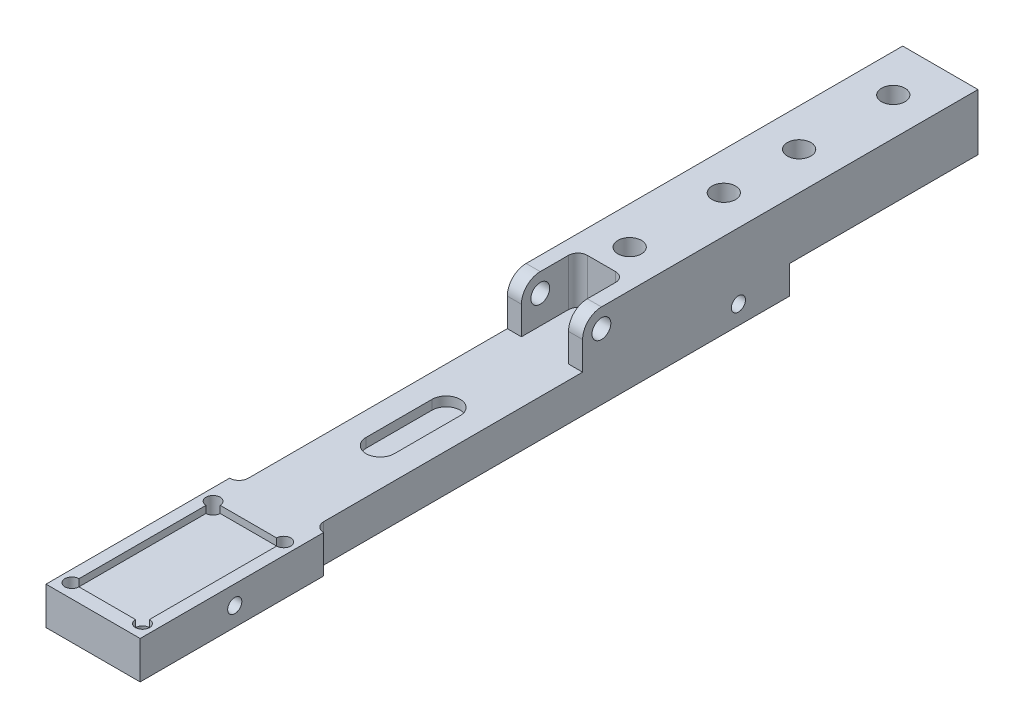
SolidWorks part; units mm, degrees
material "1060 Alloy"
ref_plane "Front Plane" through (0, 0, 0) normal (0, 0, 1) x (1, 0, 0)
ref_plane "Top Plane" through (0, 0, 0) normal (0, 1, 0) x (1, 0, 0)
ref_plane "Right Plane" through (0, 0, 0) normal (1, 0, 0) x (0, 0, -1)
sketch "Sketch1" plane through (0, 0, 0) normal (1, 0, 0) x (0, 0, -1)
  line L1 (40, -8) -> (-100, -8)
  line L2 (40, -8) -> (40, -14)
  line L3 (40, -14) -> (-100, -14)
  line L4 (-100, -8) -> (-100, -14)
  dimension "D1" = 8
  dimension "D2" = 6
  dimension "D3" = 100
  dimension "D4" = 40
extrude "Boss-Extrude1" add sketch "Sketch1" along normal mid plane 20
sketch "Sketch2" plane through (0, 0, 0) normal (1, 0, 0) x (0, 0, -1)
  line L0 (40, -8) -> (-100, -8) construction
  line L1 (-4, -8) -> (4, -8)
  line L2 (-4, -8) -> (-4, 0)
  line L3 (0, 4) -> (40, 4)
  line L4 (4, -8) -> (40, -8)
  line L5 (40, -8) -> (40, 4)
  circle A0 centre (0, 0) radius 2
  arc A1 (-4, 0) -> (0, 4) centre (0, 0) cw
  dimension "D1" = 4
  dimension "D4" = 8
  dimension "D2" = 12
  dimension "D3" = 4
extrude "Boss-Extrude2" add sketch "Sketch2" along normal mid plane 20
sketch "Sketch6" plane through (0, 0, 4) normal (0, 0, 1) x (1, 0, 0)
  line L0 (10, 4) -> (-10, 4) construction
  line L1 (-10, -8) -> (-8, -8)
  line L2 (-10, -8) -> (-10, 4)
  line L3 (-10, 4) -> (-8, 4)
  line L4 (-8, -8) -> (-8, 4)
  line L5 (0, 0) -> (0, -14.5708) construction
  line L6 (10, -8) -> (8, -8)
  line L7 (8, -8) -> (8, 4)
  line L8 (10, 4) -> (8, 4)
  line L9 (10, -8) -> (10, 4)
  dimension "D1" = 2
extrude "Cut-Extrude3" cut sketch "Sketch6" against normal through all
sketch "Sketch7" plane through (0, 4, 0) normal (0, 1, 0) x (1, 0, 0)
  line L0 (8, -4) -> (-8, -4) construction
  line L1 (-5, -4) -> (5, -4)
  line L2 (-5, -4) -> (-5, 6)
  line L3 (-3, 8) -> (3, 8)
  line L4 (5, -4) -> (5, 6)
  arc A0 (-5, 6) -> (-3, 8) centre (-3, 6) cw
  arc A1 (5, 6) -> (3, 8) centre (3, 6) ccw
  dimension "D3" = 10
  dimension "D4" = 2
  dimension "D1" = 10
  dimension "D2" = 5
extrude "Cut-Extrude4" cut sketch "Sketch7" against normal blind 10
sketch "Sketch8" plane through (0, 0, 4) normal (0, 0, 1) x (1, 0, 0)
  line L0 (8, 0) -> (8, -8) construction
  line L1 (-8, -8) -> (8, -8)
  line L2 (-8, -8) -> (-8, -6)
  line L3 (-8, -6) -> (8, -6)
  line L4 (8, -8) -> (8, -6)
  dimension "D1" = 2
extrude "Boss-Extrude3" add sketch "Sketch8" along normal blind 15
sketch "Sketch9" plane through (0, 0, 19) normal (0, 0, 1) x (1, 0, 0)
  line L0 (-10, -6) -> (10, -6)
  line L1 (-10, -8) -> (10, -8)
  line L6 (-10, -6) -> (-10, -8)
  line L10 (10, -6) -> (10, -8)
  dimension "D1" = 2
extrude "Boss-Extrude4" add sketch "Sketch9" along normal blind 81
sketch "Sketch11" plane through (0, -8, 0) normal (0, 1, 0) x (1, 0, 0)
  line L0 (-10, -59) -> (-10, -61)
  line L1 (10, 40) -> (8, 40)
  line L2 (10, 40) -> (10, -59)
  line L4 (8, 40) -> (8, -59)
  line L5 (-10, 40) -> (-8, 40)
  line L6 (-10, 40) -> (-10, -59)
  line L7 (10, -59) -> (10, -61)
  line L8 (-8, 40) -> (-8, -59)
  arc A0 (-10, -61) -> (-8, -59) centre (-10, -59) ccw
  arc A1 (8, -59) -> (10, -61) centre (10, -59) ccw
  dimension "D1" = 2
  dimension "D2" = 2
  dimension "D3" = 99
  dimension "D4" = 99
extrude "Cut-Extrude6" cut sketch "Sketch11" against normal through all both and the other way through all
sketch "Sketch12" plane through (0, 0, -40) normal (0, 0, -1) x (-1, 0, 0)
  line L1 (-8, 4) -> (-8, -14) construction
  line L2 (8, 4) -> (-8, 4)
  line L3 (8, 4) -> (8, -8)
  line L4 (8, -8) -> (-8, -8)
  line L6 (-8, 4) -> (-8, -8)
  dimension "D1" = 12
extrude "Boss-Extrude5" add sketch "Sketch12" along normal blind 40
sketch "Sketch13" plane through (0, -6, 0) normal (0, 1, 0) x (1, 0, 0)
  line L0 (0, 0) -> (0, -110.9595) construction
  line L1 (10, -100) -> (10, -61) construction
  line L2 (10, -100) -> (-10, -100) construction
  circle A0 centre (7.5, -97) radius 1.5
  circle A1 centre (7.5, -67) radius 1.5
  circle A2 centre (-7.5, -67) radius 1.5
  circle A3 centre (-7.5, -97) radius 1.5
  dimension "D1" = 3
  dimension "D2" = 3
  dimension "D3" = 30
  dimension "D4" = 2.5
  dimension "D5" = 3
  dimension "D6" = 2.5
extrude "Cut-Extrude7" cut sketch "Sketch13" against normal through all
sketch "Sketch14" plane through (0, -6, 0) normal (0, 1, 0) x (1, 0, 0)
  line L1 (-7.5, -67) -> (7.5, -67)
  line L2 (-7.5, -67) -> (-7.5, -97)
  line L3 (-7.5, -97) -> (7.5, -97)
  line L4 (7.5, -67) -> (7.5, -97)
extrude "Cut-Extrude8" cut sketch "Sketch14" against normal blind 1.5
sketch "Sketch15" plane through (0, -6, 0) normal (0, 1, 0) x (1, 0, 0)
  line L0 (0, 0) -> (0, -108.5535) construction
  line L1 (10, -100) -> (-10, -100) construction
  line L2 (3, -25) -> (3, -39)
  line L3 (-3, -25) -> (-3, -39)
  arc A0 (-3, -39) -> (3, -39) centre (0, -39) ccw
  arc A1 (3, -25) -> (-3, -25) centre (0, -25) ccw
  dimension "D3" = 6
  dimension "D4" = 6
  dimension "D1" = 61
  dimension "D2" = 14
extrude "Cut-Extrude9" cut sketch "Sketch15" against normal blind 2
sketch "Sketch16" plane through (0, -14, 0) normal (0, -1, 0) x (1, 0, 0)
  line L0 (0, 0) -> (0, 106.7596) construction
  line L1 (10, 100) -> (-10, 100) construction
  circle A0 centre (0, -34) radius 2.5
  circle A1 centre (0, -14) radius 2.5
  dimension "D2" = 5
  dimension "D3" = 5
  dimension "D1" = 20
  dimension "D4" = 114
extrude "Cut-Extrude10" cut sketch "Sketch16" against normal through all
sketch "Sketch17" plane through (0, -8, 0) normal (0, -1, 0) x (1, 0, 0)
  line L0 (0, 0) -> (0, -86.9839) construction
  line L1 (8, -80) -> (-8, -80) construction
  circle A0 centre (0, -70) radius 2.5
  circle A1 centre (0, -50) radius 2.5
  dimension "D1" = 5
  dimension "D2" = 5
  dimension "D3" = 10
  dimension "D4" = 20
extrude "Cut-Extrude11" cut sketch "Sketch17" against normal through all
sketch "Sketch18" plane through (8, 0, 0) normal (1, 0, 0) x (0, 0, -1)
  line L0 (40, -14) -> (-59, -14) construction
  circle A0 centre (29.1, -10) radius 1.5
  dimension "D1" = 3
  dimension "D2" = 4
  dimension "D3" = 29.1
extrude "Cut-Extrude12" cut sketch "Sketch18" against normal blind 15
sketch "Sketch19" plane through (10, 0, 0) normal (1, 0, 0) x (0, 0, -1)
  line L0 (-100, -14) -> (-61, -14) construction
  circle A0 centre (-79.9, -10) radius 1.5
  dimension "D2" = 3
  dimension "D1" = 4
  dimension "D3" = 79.9
extrude "Cut-Extrude13" cut sketch "Sketch19" against normal blind 15
